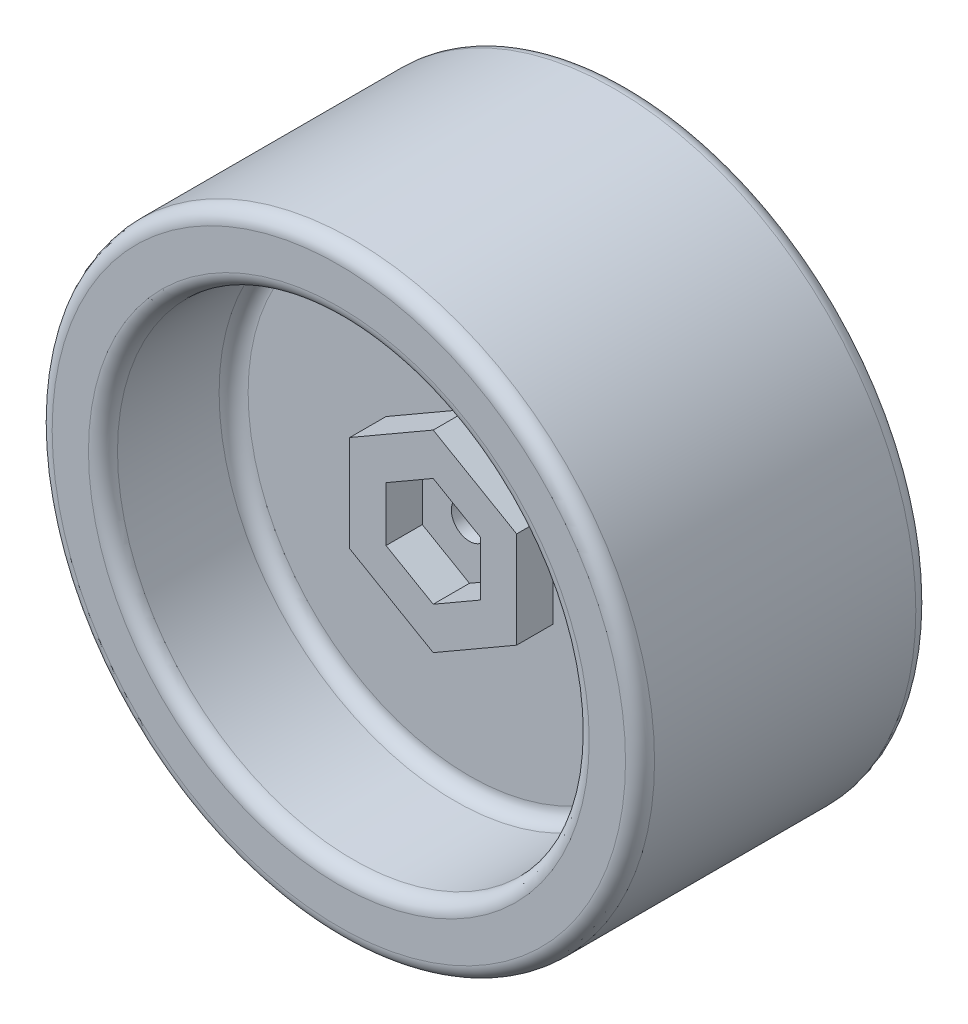
SolidWorks part; units mm, degrees
ref_plane "Front Plane" through (0, 0, 0) normal (0, 0, 1) x (1, 0, 0)
ref_plane "Top Plane" through (0, 0, 0) normal (0, 1, 0) x (1, 0, 0)
ref_plane "Right Plane" through (0, 0, 0) normal (1, 0, 0) x (0, 0, -1)
sketch "Sketch1" plane through (0, 0, 0) normal (0, 0, 1) x (1, 0, 0)
  circle A0 centre (0, 0) radius 41.5
  dimension "D1" = 83
extrude "Boss-Extrude1" add sketch "Sketch1" along normal blind 40
sketch "Sketch2" plane through (0, 0, 40) normal (0, 0, 1) x (1, 0, 0)
  circle A0 centre (0, 0) radius 2.5
  dimension "D1" = 5
extrude "Cut-Extrude1" cut sketch "Sketch2" against normal through all
sketch "Sketch4" plane through (0, 0, 0) normal (0, 0, -1) x (-1, 0, 0)
  circle A0 centre (0, 0) radius 32.5
extrude "Cut-Extrude2" cut sketch "Sketch4" against normal blind 18
sketch "Sketch5" plane through (0, 0, 40) normal (0, 0, 1) x (1, 0, 0)
  circle A0 centre (0, 0) radius 32.5
extrude "Cut-Extrude3" cut sketch "Sketch5" against normal blind 18
sketch "Sketch6" plane through (0, 0, 22) normal (0, 0, 1) x (1, 0, 0)
  line L1 (0, 6.9282) -> (-6, 3.4641)
  line L2 (-6, 3.4641) -> (-6, -3.4641)
  line L3 (-6, -3.4641) -> (0, -6.9282)
  line L4 (0, -6.9282) -> (6, -3.4641)
  line L5 (6, -3.4641) -> (6, 3.4641)
  line L6 (6, 3.4641) -> (0, 6.9282)
  circle A0 centre (0, 0) radius 2.5
  circle A1 centre (0, 0) radius 6 construction
  dimension "D1" = 12
extrude "Boss-Extrude2" add sketch "Sketch6" along normal blind 5
sketch "Sketch7" plane through (0, 0, 27) normal (0, 0, 1) x (1, 0, 0)
  circle A0 centre (0, 0) radius 2.5
  circle A1 centre (0, 0) radius 5.75
  dimension "D1" = 11.5
extrude "Boss-Extrude3" add sketch "Sketch7" along normal blind 17
fillet "Fillet3" radius 2 6 edges at (-32.5, 0, 18) (32.5, 0, 22) (32.5, 0, 40) (-32.5, 0, 0) (41.5, 0, 0) (41.5, 0, 40)
sketch "Sketch8" plane through (0, 0, 22) normal (0, 0, 1) x (1, 0, 0)
  line L0 (6.5, 3.7528) -> (0, 7.5056)
  line L1 (0, 7.5056) -> (-6.5, 3.7528)
  line L2 (-6.5, 3.7528) -> (-6.5, -3.7528)
  line L3 (-6.5, -3.7528) -> (0, -7.5056)
  line L4 (0, -7.5056) -> (6.5, -3.7528)
  line L5 (6.5, -3.7528) -> (6.5, 3.7528)
  line L6 (11.5, 6.6395) -> (0, 13.2791)
  line L7 (0, 13.2791) -> (-11.5, 6.6395)
  line L8 (-11.5, 6.6395) -> (-11.5, -6.6395)
  line L9 (-11.5, -6.6395) -> (0, -13.2791)
  line L10 (0, -13.2791) -> (11.5, -6.6395)
  line L11 (11.5, -6.6395) -> (11.5, 6.6395)
  dimension "D1" = 5
extrude "Boss-Extrude4" add sketch "Sketch8" along normal blind 5
sketch "Sketch9" plane through (0, 0, 44) normal (0, 0, 1) x (1, 0, 0)
  line L1 (0, 7.2477) -> (-6.2767, 3.6238)
  line L2 (-6.2767, 3.6238) -> (-6.2767, -3.6238)
  line L3 (-6.2767, -3.6238) -> (0, -7.2477)
  line L4 (0, -7.2477) -> (6.2767, -3.6238)
  line L5 (6.2767, -3.6238) -> (6.2767, 3.6238)
  line L6 (6.2767, 3.6238) -> (0, 7.2477)
  circle A0 centre (0, 0) radius 6.2767 construction
extrude "Cut-Extrude4" cut sketch "Sketch9" against normal blind 22
